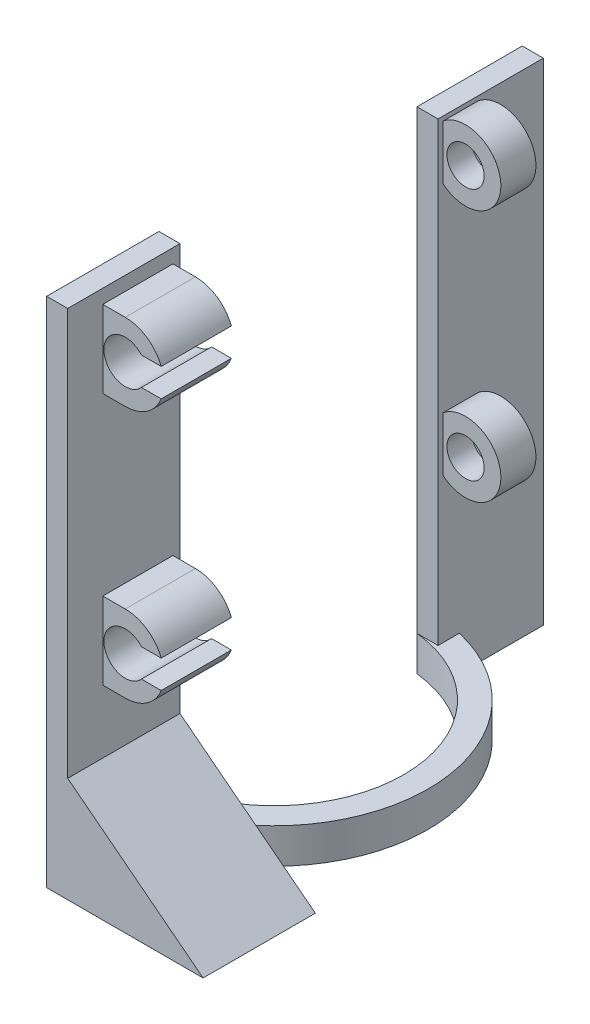
SolidWorks part; units mm, degrees
ref_plane "Front Plane" through (0, 0, 0) normal (0, 0, 1) x (1, 0, 0)
ref_plane "Top Plane" through (0, 0, 0) normal (0, 1, 0) x (1, 0, 0)
ref_plane "Right Plane" through (0, 0, 0) normal (1, 0, 0) x (0, 0, -1)
sketch "Sketch1" plane through (0, 0, 0) normal (0, 0, 1) x (1, 0, 0)
  line L0 (0, 5.5) -> (-3.1995, 5.5)
  line L1 (-3.1995, 5.5) -> (-3.1995, -5.5)
  line L2 (-3.1995, -5.5) -> (0, -5.5)
  line L3 (-20.8389, -18) -> (24.3467, -18) construction
  line L4 (2.3027, 2) -> (5.1235, 2)
  line L5 (2.3027, -2) -> (5.1235, -2)
  line L6 (2.3027, -34) -> (5.1235, -34)
  line L7 (2.3027, -38) -> (5.1235, -38)
  line L8 (-3.1995, -30.5) -> (0, -30.5)
  line L9 (-3.1995, -41.5) -> (-3.1995, -30.5)
  line L10 (0, -41.5) -> (-3.1995, -41.5)
  arc A0 (2.3027, 2) -> (2.3027, -2) centre (0, 0) ccw
  arc A1 (0, -5.5) -> (5.1235, -2) centre (0, 0) ccw
  arc A2 (5.1235, 2) -> (0, 5.5) centre (0, 0) ccw
  arc A3 (5.1235, -38) -> (0, -41.5) centre (0, -36) cw
  arc A4 (0, -30.5) -> (5.1235, -34) centre (0, -36) cw
  arc A5 (2.3027, -38) -> (2.3027, -34) centre (0, -36) cw
  point P21 (0, 0)
  dimension "D1" = 6.1
  dimension "D2" = 11
  dimension "D3" = 18
  dimension "D4" = 2
  dimension "D5" = 2
extrude "Boss-Extrude1" add sketch "Sketch1" along normal blind 10
sketch "Sketch2" plane through (-3.1995, 0, 0) normal (-1, 0, 0) x (0, 0, 1)
  line L0 (0, 5.5) -> (0, -5.5) construction
  line L1 (-1, 7.5) -> (15, 7.5)
  line L2 (-1, 7.5) -> (-1, -50.5)
  line L3 (-1, -50.5) -> (15, -50.5)
  line L4 (15, 7.5) -> (15, -50.5)
  line L5 (10, 5.5) -> (10, -5.5) construction
  line L6 (10, 5.5) -> (0, 5.5) construction
  line L7 (10, -41.5) -> (0, -41.5) construction
  dimension "D1" = 1
  dimension "D2" = 5
  dimension "D3" = 2
  dimension "D4" = 9
extrude "Boss-Extrude2" add sketch "Sketch2" along normal blind 3
ref_plane "Plane1" through (0, -65.5, 0) normal (0, -1, 0) x (-1, 0, 0)
sketch "Sketch3" plane through (0, -65.5, 0) normal (0, -1, 0) x (-1, 0, 0)
  line L1 (6.1995, 1) -> (-16.0943, 1)
  line L2 (6.1995, 1) -> (6.1995, -15)
  line L3 (6.1995, -15) -> (-16.0943, -15)
  line L4 (-16.0943, 1) -> (-16.0943, -15)
loft "Loft1" add profiles "Sketch3" section face at (-4.6995, -50.5, 7) section "Sketch3"
sketch "Sketch4" plane through (0, -65.5, 0) normal (0, -1, 0) x (1, 0, 0)
  line L0 (-6.1995, 15) -> (-6.1995, -1) construction
  line L2 (-6.1995, 2.5173) -> (-6.1995, -1)
  line L3 (-6.1995, -37.7831) -> (-6.1995, -41.3005)
  arc A0 (-6.1995, -37.7831) -> (-6.1995, -1) centre (-8.1995, -19.3916) ccw
  arc A1 (-6.1995, -41.3005) -> (-6.1995, 2.5173) centre (-8.1995, -19.3916) ccw
  point P1 (0, 0)
  point P5 (0, 0)
  dimension "D1" = 18.5
  dimension "D3" = 22
  dimension "D2" = 2
extrude "Boss-Extrude3" add sketch "Sketch4" against normal blind 5 separate body
sketch "Sketch5" plane through (0, -65.5, 0) normal (0, -1, 0) x (1, 0, 0)
  line L1 (-6.1995, -37.7831) -> (-3.1995, -37.7831)
  line L2 (-6.1995, -37.7831) -> (-6.1995, -52.7831)
  line L3 (-6.1995, -52.7831) -> (-3.1995, -52.7831)
  line L4 (-3.1995, -37.7831) -> (-3.1995, -52.7831)
  dimension "D1" = 3
  dimension "D2" = 15
extrude "Boss-Extrude4" add sketch "Sketch5" against normal blind 70
sketch "Sketch6" plane through (0, 0, 0) normal (0, 0, -1) x (-1, 0, 0)
  circle A0 centre (0, 0) radius 2.65
  dimension "D1" = 5.3
sketch "Sketch7" plane through (0, 0, 0) normal (0, 0, -1) x (-1, 0, 0)
  circle A0 centre (0, 0) radius 5.0297
extrude "Boss-Extrude5" add sketch "Sketch7" along normal blind 5 from offset 38.5 separate body
extrude "Cut-Extrude1" cut sketch "Sketch6" along normal blind 42
sketch "Sketch8" plane through (0, 0, -42) normal (0, 0, 1) x (1, 0, 0)
  circle A0 centre (-1.5, 0) radius 1
  circle A1 centre (1.5, 0) radius 1
  dimension "D1" = 2
  dimension "D2" = 2
  dimension "D3" = 1.5
  dimension "D4" = 1.5
extrude "Cut-Extrude2" cut sketch "Sketch8" against normal up to surface (1.5 mm away) up to face at (-5.0297, 0, -43.5)
pattern_linear "LPattern1" count 2 spacing 36 along (0, -1, 0) of "Boss-Extrude5"
equation "\"D5@Sketch1\"=\"D4@Sketch1\""
equation "\"D2@Sketch8\"=\"D1@Sketch8\""
equation "\"D4@Sketch8\"=\"D3@Sketch8\""
